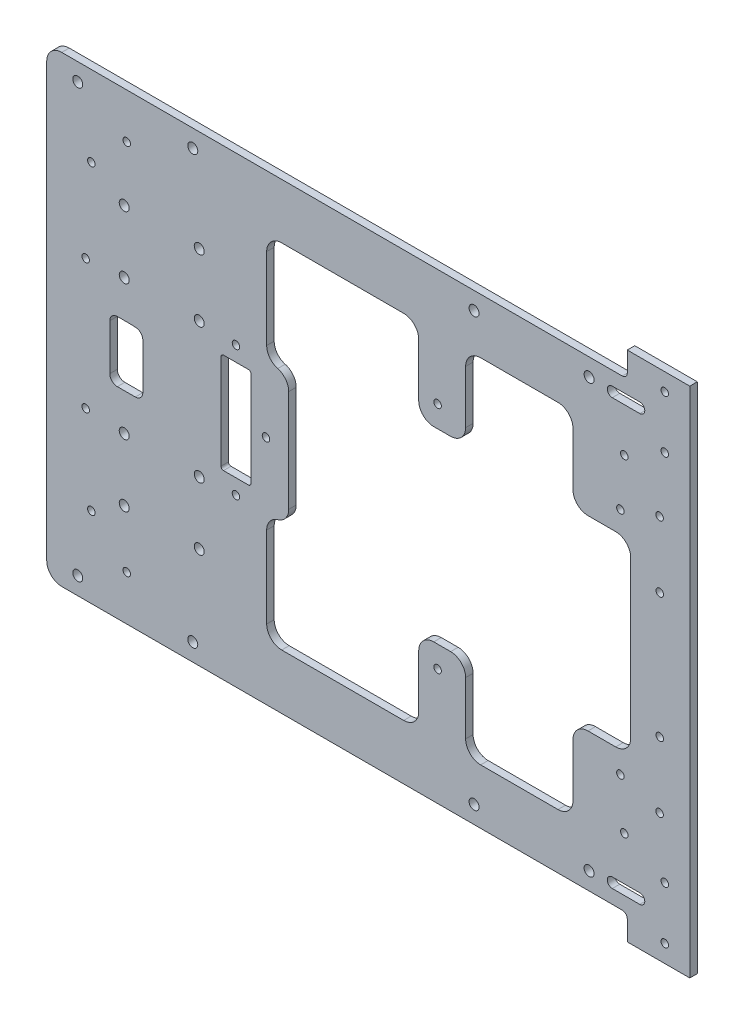
SolidWorks part; units mm, degrees
ref_plane "前视基准面" through (0, 0, 0) normal (0, 0, 1) x (1, 0, 0)
ref_plane "上视基准面" through (0, 0, 0) normal (0, 1, 0) x (1, 0, 0)
ref_plane "右视基准面" through (0, 0, 0) normal (1, 0, 0) x (0, 0, -1)
sketch "草图2" plane through (0, 0, 0) normal (0, 0, 1) x (1, 0, 0)
  line L18 (0, 0) -> (340.6218, 0) construction
  line L19 (0, -92.5) -> (0, 92.5)
  line L20 (0, 92.5) -> (232.18, 92.5)
  line L21 (232.18, 92.5) -> (232.18, 102.5)
  line L22 (232.18, 102.5) -> (257.18, 102.5)
  line L23 (257.18, 102.5) -> (257.18, -102.5)
  line L24 (232.18, -102.5) -> (257.18, -102.5)
  line L25 (232.18, -92.5) -> (232.18, -102.5)
  line L26 (0, -92.5) -> (232.18, -92.5)
  point P8 (257.18, 0)
  dimension "D1" = 92.5
  dimension "D2" = 257.18
  dimension "D3" = 10
  dimension "D4" = 25
extrude "凸台-拉伸1" add sketch "草图2" along normal blind 3 contours L20 L21 L22 L23 L24 L25 L26 L19
fillet "圆角1" radius 6 1 edges at (0, -92.5, 1.5)
fillet "圆角2" radius 6 1 edges at (0, 92.5, 1.5)
fillet "圆角3" radius 2 1 edges at (232.18, -92.5, 1.5)
fillet "圆角4" radius 2 1 edges at (232.18, 92.5, 1.5)
sketch "草图3" plane through (0, 0, 0) normal (0, 0, -1) x (-1, 0, 0)
  line L1 (-6, 92.5) -> (-230.18, 92.5) construction
  line L2 (-257.18, 102.5) -> (-257.18, -102.5) construction
  line L3 (0, 0) -> (-52.5724, 0) construction
  line L4 (-6, 92.5) -> (-230.18, 92.5) construction
  circle A2 centre (-216.91, 85.5) radius 2
  circle A3 centre (-170.91, 85.5) radius 2
  circle A4 centre (-170.91, -85.5) radius 2
  circle A5 centre (-216.91, -85.5) radius 2
  circle A8 centre (-12.41, 85.5) radius 2
  circle A9 centre (-58.41, 85.5) radius 2
  circle A10 centre (-58.41, -85.5) radius 2
  circle A11 centre (-12.41, -85.5) radius 2
  dimension "D5" = 46
  dimension "D6" = 4
  dimension "D7" = 4
  dimension "D2" = 4
  dimension "D3" = 4
  dimension "D4" = 7
  dimension "D8" = 40.27
  dimension "D9" = 46
  dimension "D10" = 7
  dimension "D11" = 204.5
extrude "切除-拉伸1" cut sketch "草图3" against normal blind 3
sketch "草图4" plane through (0, 0, 0) normal (0, 0, -1) x (-1, 0, 0)
  line L0 (-257.18, 0) -> (0, 0) construction
  line L1 (-257.18, 102.5) -> (-257.18, -102.5) construction
  line L3 (-232.18, -102.5) -> (-257.18, -102.5) construction
  line L4 (-257.18, -39.2789) -> (-203.9589, -92.5) construction
  line L5 (-6, -92.5) -> (-230.18, -92.5) construction
  line L6 (-247.18, -74.5) -> (-247.18, -95.5) construction
  line L7 (-247.18, -85) -> (-225.7964, -85) construction
  line L8 (-237.18, -85) -> (-226.18, -85) construction
  line L9 (-237.18, -83) -> (-226.18, -83)
  line L10 (-237.18, -87) -> (-226.18, -87)
  line L11 (-237.18, 85) -> (-226.18, 85) construction
  line L12 (-237.18, 83) -> (-226.18, 83)
  line L13 (-237.18, 87) -> (-226.18, 87)
  line L14 (0, -42.5) -> (-50, -92.5) construction
  line L15 (0, -86.5) -> (0, 86.5) construction
  circle A0 centre (-247.18, -74.5) radius 1.5
  circle A1 centre (-247.18, -95.5) radius 1.5
  circle A2 centre (-247.18, 95.5) radius 1.5
  circle A3 centre (-247.18, 74.5) radius 1.5
  circle A4 centre (-245.123, -51.3359) radius 1.5
  circle A5 centre (-230.9809, -65.4781) radius 1.5
  circle A6 centre (-230.9809, 65.4781) radius 1.5
  circle A7 centre (-245.123, 51.3359) radius 1.5
  arc A8 (-237.18, -83) -> (-237.18, -87) centre (-237.18, -85) ccw
  arc A9 (-226.18, -87) -> (-226.18, -83) centre (-226.18, -85) ccw
  arc A10 (-237.18, 83) -> (-237.18, 87) centre (-237.18, 85) cw
  arc A11 (-226.18, 87) -> (-226.18, 83) centre (-226.18, 85) cw
  circle A12 centre (-17.8579, -60.3579) radius 1.5
  circle A13 centre (-32, -74.5) radius 1.5
  circle A14 centre (-32, 74.5) radius 1.5
  circle A15 centre (-17.8579, 60.3579) radius 1.5
  point P31 (-231.68, -85)
  point P38 (-231.68, 85)
  dimension "D1" = 3
  dimension "D2" = 3
  dimension "D3" = 10
  dimension "D5" = 7
  dimension "D7" = 3
  dimension "D8" = 3
  dimension "D9" = 20
  dimension "D10" = 2
  dimension "D14" = 20
  dimension "D15" = 3
  dimension "D16" = 3
  dimension "D4" = 21
  dimension "D6" = 45
  dimension "D11" = 11
  dimension "D12" = 10
  dimension "D13" = 45
  dimension "D17" = 50
  dimension "D18" = 18
extrude "切除-拉伸2" cut sketch "草图4" against normal blind 10
sketch "草图5" plane through (0, 0, 0) normal (0, 0, -1) x (-1, 0, 0)
  line L0 (-257.18, 0) -> (0, 0) construction
  line L1 (-257.18, 102.5) -> (-257.18, -102.5) construction
  line L2 (0, -86.5) -> (0, 86.5) construction
  circle A0 centre (-61, -52) radius 2
  circle A1 centre (-61, -27) radius 2
  circle A2 centre (-31, -27) radius 2
  circle A3 centre (-31, -52) radius 2
  circle A4 centre (-31, 52) radius 2
  circle A5 centre (-31, 27) radius 2
  circle A6 centre (-61, 27) radius 2
  circle A7 centre (-61, 52) radius 2
  dimension "D1" = 4
  dimension "D2" = 4
  dimension "D3" = 4
  dimension "D4" = 4
  dimension "D6" = 25
  dimension "D7" = 30
  dimension "D5" = 31
  dimension "D8" = 27
extrude "切除-拉伸3" cut sketch "草图5" against normal blind 10
sketch "草图7" plane through (0, 0, 0) normal (0, 0, 1) x (1, 0, 0)
  line L126 (70.691, 20) -> (80.691, 20) construction
  line L127 (69.691, -19) -> (69.691, 19) construction
  line L128 (81.691, 19) -> (81.691, -19) construction
  line L129 (80.691, -20) -> (70.691, -20) construction
  line L130 (70.691, 20) -> (80.691, 20)
  line L131 (69.691, -19) -> (69.691, 19)
  line L132 (81.691, 19) -> (81.691, -19)
  line L133 (80.691, -20) -> (70.691, -20)
  circle A20 centre (15.5938, 26) radius 1.5
  circle A21 centre (15.5938, -26) radius 1.5
  circle A22 centre (75.691, -26) radius 1.5
  circle A23 centre (75.691, 26) radius 1.5
  circle A24 centre (87.691, 0) radius 1.5
  arc A25 (81.691, 19) -> (80.691, 20) centre (80.691, 19) ccw construction
  arc A26 (70.691, 20) -> (69.691, 19) centre (70.691, 19) ccw construction
  arc A27 (80.691, -20) -> (81.691, -19) centre (80.691, -19) ccw construction
  arc A28 (69.691, -19) -> (70.691, -20) centre (70.691, -19) ccw construction
  arc A29 (81.691, 19) -> (80.691, 20) centre (80.691, 19) ccw
  arc A30 (70.691, 20) -> (69.691, 19) centre (70.691, 19) ccw
  arc A31 (80.691, -20) -> (81.691, -19) centre (80.691, -19) ccw
  arc A32 (69.691, -19) -> (70.691, -20) centre (70.691, -19) ccw
sketch "草图9" plane through (0, 0, 0) normal (0, 0, -1) x (-1, 0, 0)
  line L0 (-257.18, 0) -> (0, 0) construction
  line L5 (-156.3243, -45.9) -> (-229.4243, -45.9) construction
  line L6 (-156.3243, -45.9) -> (-156.3243, 45.9) construction
  line L7 (-156.3243, 45.9) -> (-229.4243, 45.9) construction
  line L8 (-229.4243, -45.9) -> (-229.4243, 45.9) construction
  circle A0 centre (-229.4243, -45.9) radius 1.5
  circle A1 centre (-229.4243, 45.9) radius 1.5
  circle A2 centre (-156.3243, -45.9) radius 1.5
  circle A3 centre (-156.3243, 45.9) radius 1.5
  point P11 (-156.3243, 0)
  dimension "D1" = 3
  dimension "D2" = 3
  dimension "D3" = 3
  dimension "D4" = 3
  dimension "D5" = 73.1
  dimension "D6" = 91.8
extrude "切除-拉伸5" cut sketch "草图9" against normal up to next
sketch "草图10" plane through (0, 0, 3) normal (0, 0, 1) x (1, 0, 0)
  line L0 (87.9687, 39.6611) -> (87.9687, 25.9622)
  line L1 (87.9687, 25.9622) -> (96.7726, 25.9622)
  line L2 (96.7726, 25.9622) -> (96.7726, -25.9622)
  line L3 (257.18, 0) -> (0, 0) construction
  line L4 (96.7726, 0) -> (233.5537, 0) construction
  line L5 (233.5537, -37.281) -> (233.5537, 37.281)
  line L7 (87.9687, 39.6611) -> (87.9687, 70.5)
  line L8 (87.9687, 70.5) -> (148.7727, 70.5)
  line L9 (148.7727, 70.5) -> (148.7727, 37.281)
  line L10 (148.7727, 37.281) -> (167.5322, 37.281)
  line L11 (167.5322, 37.281) -> (167.5322, 70.5)
  line L12 (167.5322, 70.5) -> (210.4736, 70.5)
  line L13 (210.4736, 70.5) -> (210.4736, 37.281)
  line L14 (210.4736, 37.281) -> (233.5537, 37.281)
  line L15 (210.4736, -37.281) -> (233.5537, -37.281)
  line L16 (210.4736, -70.5) -> (210.4736, -37.281)
  line L17 (167.5322, -70.5) -> (210.4736, -70.5)
  line L18 (167.5322, -37.281) -> (167.5322, -70.5)
  line L19 (148.7727, -37.281) -> (167.5322, -37.281)
  line L20 (148.7727, -70.5) -> (148.7727, -37.281)
  line L21 (87.9687, -70.5) -> (148.7727, -70.5)
  line L22 (87.9687, -39.6611) -> (87.9687, -70.5)
  line L23 (87.9687, -25.9622) -> (96.7726, -25.9622)
  line L24 (87.9687, -39.6611) -> (87.9687, -25.9622)
  line L25 (6, 92.5) -> (230.18, 92.5) construction
  dimension "D1" = 22
  dimension "D2" = 22
extrude "切除-拉伸6" cut sketch "草图10" against normal up to next
fillet "圆角6" radius 6 8 edges at (233.5537, -37.281, 1.5) (233.5537, 37.281, 1.5) (210.4736, 37.281, 1.5) (210.4736, -37.281, 1.5) (210.4736, 70.5, 1.5) (167.5322, 70.5, 1.5) (167.5322, -70.5, 1.5) (210.4736, -70.5, 1.5)
fillet "圆角7" radius 6 10 edges at (167.5322, -37.281, 1.5) (148.7727, -37.281, 1.5) (148.7727, -70.5, 1.5) (87.9687, -70.5, 1.5) (87.9687, -25.9622, 1.5) (87.9687, 25.9622, 1.5) (87.9687, 70.5, 1.5) (148.7727, 70.5, 1.5) (148.7727, 37.281, 1.5) (167.5322, 37.281, 1.5)
fillet "圆角8" radius 6 2 edges at (96.7726, 25.9622, 1.5) (96.7726, -25.9622, 1.5)
extrude "切除-拉伸8" cut sketch "草图7" along normal up to next
sketch "草图12" plane through (0, 0, 3) normal (0, 0, 1) x (1, 0, 0)
  line L1 (32.93, -12.15) -> (35.4258, -12.15)
  line L2 (38.4258, -9.15) -> (38.4258, 9.0526)
  line L3 (35.5402, 12.0504) -> (32.93, 12.15)
  line L15 (32.93, 12.15) -> (28.23, 12.15)
  line L16 (25.23, 9.15) -> (25.23, 8.15)
  line L17 (25.23, 8.15) -> (25.23, 1.2)
  line L28 (25.23, 1.2) -> (25.23, -1.2)
  line L29 (25.23, -1.2) -> (25.23, -8.15)
  line L30 (25.23, -8.15) -> (25.23, -9.15)
  line L31 (28.23, -12.15) -> (32.93, -12.15)
  arc A0 (35.5402, 12.0504) -> (38.4258, 9.0526) centre (35.4258, 9.0526) cw
  arc A1 (25.23, 9.15) -> (28.23, 12.15) centre (28.23, 9.15) cw
  arc A4 (28.23, -12.15) -> (25.23, -9.15) centre (28.23, -9.15) cw
  arc A5 (38.4258, -9.15) -> (35.4258, -12.15) centre (35.4258, -9.15) cw
  dimension "D1" = 3
  dimension "D2" = 3
  dimension "D3" = 3
  dimension "D4" = 3
extrude "切除-拉伸9" cut sketch "草图12" against normal up to next contours L15 A1 L16 L17 L28 L29 L30 A4 L31 L1 A5 L2 A0 L3
sketch "草图13" plane through (0, 0, 3) normal (0, 0, 1) x (1, 0, 0)
  line L0 (257.18, 0) -> (0, 0) construction
  line L1 (257.18, 102.5) -> (257.18, -102.5) construction
  line L2 (0, 0) -> (107.8258, 0) construction
  circle A0 centre (245.18, 25) radius 1.5
  circle A1 centre (245.18, -25) radius 1.5
  dimension "D1" = 3
  dimension "D2" = 25
  dimension "D3" = 12
extrude "切除-拉伸10" cut sketch "草图13" against normal up to next
equation "\"25、\"=20.7"
